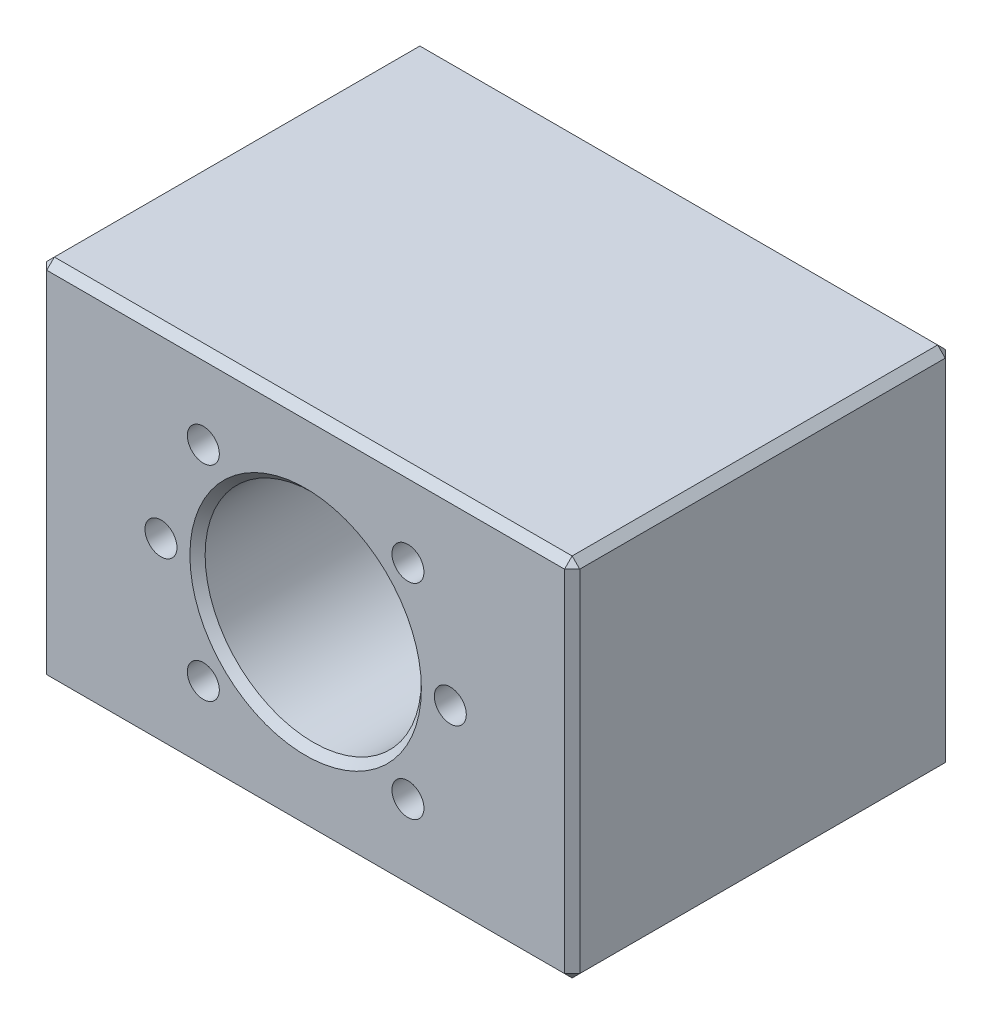
SolidWorks part; units mm, degrees
ref_plane "Plan de face" through (0, 0, 0) normal (0, 0, 1) x (1, 0, 0)
ref_plane "Plan de dessus" through (0, 0, 0) normal (0, 1, 0) x (1, 0, 0)
ref_plane "Plan de droite" through (0, 0, 0) normal (1, 0, 0) x (0, 0, -1)
ref_plane "Plan1" through (0, -24, 0) normal (0, -1, 0) x (1, 0, 0)
sketch "Esquisse1" plane through (0, -24, 0) normal (0, -1, 0) x (1, 0, 0)
  line L0 (-35, -25) -> (35, -25)
  line L1 (35, -25) -> (35, 25)
  line L2 (35, 25) -> (-35, 25)
  line L3 (-35, 25) -> (-35, -25)
extrude "Boss.-Extru.1" add sketch "Esquisse1" against normal blind 48
hole_wizard "Dégagement M251" positions "Esquisse3" profile "Esquisse2" hole size "M25" standard "Ansi Metric"
sketch "Esquisse3" plane through (0, 0, -25) normal (0, 0, -1) x (-1, 0, 0)
  point P0 (0, 0)
sketch "Esquisse2" plane through (0, 0, -25) normal (1, 0, 0) x (0, 1, 0)
  line L0 (0, 0) -> (0, 50)
  line L1 (0, 50) -> (14.2, 50)
  line L2 (14.2, 50) -> (14.2, 0)
  line L5 (14.2, 0) -> (0, 0)
  line L11 (0, -6.35) -> (0, 107.95) construction
  dimension "Diamètre du perçage jusqu'au prochain" = 28.4
  dimension "Profondeur du perçage jusqu'au prochain" = 50
hole_wizard "Diamètre du perçage Ø4.2 (4.2)1" positions "Esquisse5" profile "Esquisse4" hole size "Ø4.2" standard "Ansi Metric"
sketch "Esquisse5" plane through (0, 0, 25) normal (0, 0, 1) x (1, 0, 0)
  point P0 (13.435, -13.435)
  point P1 (13.435, 13.435)
  point P2 (19, 0)
  point P3 (-13.435, 13.435)
  point P4 (-13.435, -13.435)
  point P5 (-19, 0)
sketch "Esquisse4" plane through (13.435, -13.435, 25) normal (1, 0, 0) x (0, -1, 0)
  line L0 (0, 0) -> (0, 15.2618)
  line L1 (0, 15.2618) -> (2.1, 14)
  line L2 (2.1, 14) -> (2.1, 0)
  line L5 (2.1, 0) -> (0, 0)
  line L10 (0, 15.2618) -> (-2.1, 14) construction
  line L11 (0, -6.35) -> (0, 107.95) construction
  dimension "Diamètre du perçage" = 4.2
  dimension "Profondeur du perçage" = 14
  dimension "Angle de pointe" = 118
hole_wizard "Chambrage pour vis à tête hexagonale M81" positions "Esquisse7" profile "Esquisse6" counterbore size "M8" standard "Ansi Metric"
sketch "Esquisse7" plane through (0, -24, 0) normal (0, -1, 0) x (1, 0, 0)
  point P0 (25, 5)
  point P1 (25, -15)
  point P2 (-25, 5)
  point P3 (-25, -15)
sketch "Esquisse6" plane through (25, -24, 5) normal (1, 0, 0) x (0, 0, -1)
  line L0 (0, 0) -> (0, 22.5837)
  line L1 (0, 22.5837) -> (4.3, 20)
  line L2 (4.3, 20) -> (4.3, 2)
  line L3 (4.3, 2) -> (7, 2)
  line L4 (7, 2) -> (7, 0)
  line L5 (7, 0) -> (0, 0)
  line L10 (0, 22.5837) -> (-4.3, 20) construction
  line L11 (0, -6.35) -> (0, 107.95) construction
  dimension "Diamètre du perçage" = 8.6
  dimension "Profondeur du perçage" = 20
  dimension "Diamètre du chambrage" = 14
  dimension "Profondeur du chambrage" = 2
  dimension "Angle de pointe" = 118
chamfer "Chanfrein1" distance 0.5 angle 45 4 edges at (25, -24, -22) (-25, -24, -2) (-25, -24, -22) (25, -24, -2)
chamfer "Chanfrein2" distance 1 angle 45 14 edges at (35, 0, -25) (0, -24, -25) (35, 24, 0) (35, 0, 25) (35, -24, 0) (0, 24, -25) (-35, 0, -25) (-35, -24, 0) (0, 24, 25) (0, -24, 25) (-35, 24, 0) (-35, 0, 25) (-14.2, 0, 25) (-14.2, 0, -25)
